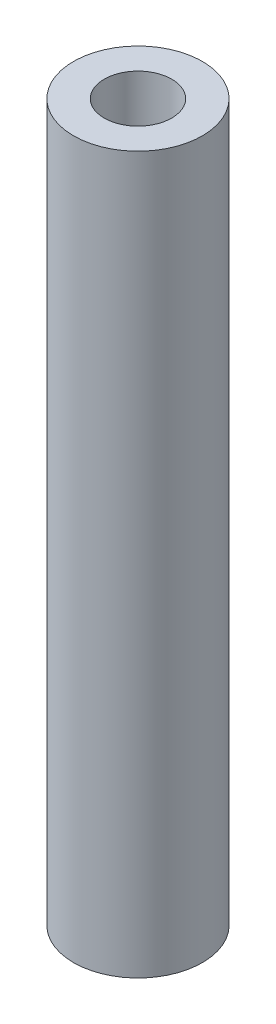
SolidWorks part; units mm, degrees
ref_plane "Front Plane" through (0, 0, 0) normal (0, 0, 1) x (1, 0, 0)
ref_plane "Top Plane" through (0, 0, 0) normal (0, 1, 0) x (1, 0, 0)
ref_plane "Right Plane" through (0, 0, 0) normal (1, 0, 0) x (0, 0, -1)
sketch "Sketch1" plane through (0, 0, 0) normal (0, 1, 0) x (1, 0, 0)
  circle A0 centre (0, 0) radius 3.15
  circle A1 centre (0, 0) radius 1.65
  dimension "D1" = 1.5
  dimension "D2" = 3.3
extrude "Boss-Extrude1" add sketch "Sketch1" along normal blind 35
